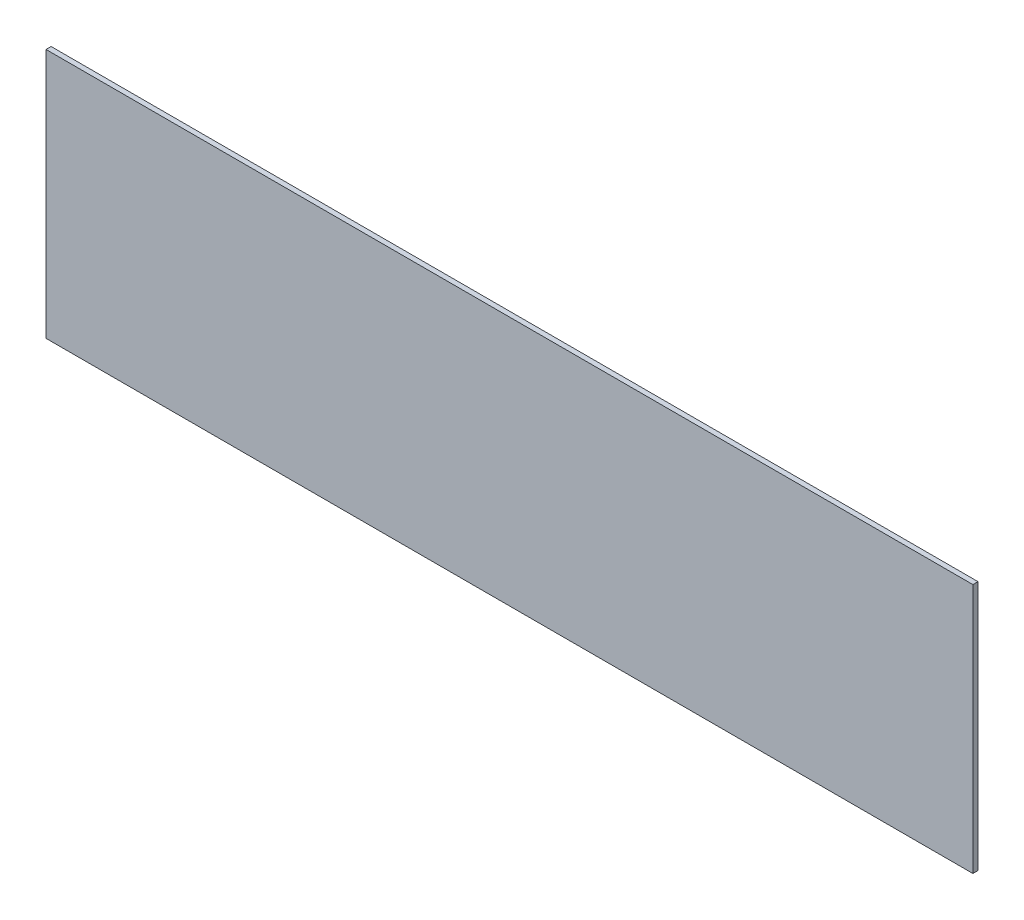
SolidWorks part; units mm, degrees
ref_plane "Front Plane" through (0, 0, 0) normal (0, 0, 1) x (1, 0, 0)
ref_plane "Top Plane" through (0, 0, 0) normal (0, 1, 0) x (1, 0, 0)
ref_plane "Right Plane" through (0, 0, 0) normal (1, 0, 0) x (0, 0, -1)
sketch "Sketch1" plane through (0, 0, 0) normal (0, 0, 1) x (1, 0, 0)
  line L0 (0, 0) -> (0, 49)
  line L1 (0, 49) -> (181.51, 49)
  line L2 (181.51, 49) -> (181.51, 0)
  line L3 (181.51, 0) -> (0, 0)
  dimension "D1" = 49
  dimension "D2" = 181.51
extrude "Boss-Extrude1" add sketch "Sketch1" along normal blind 1
